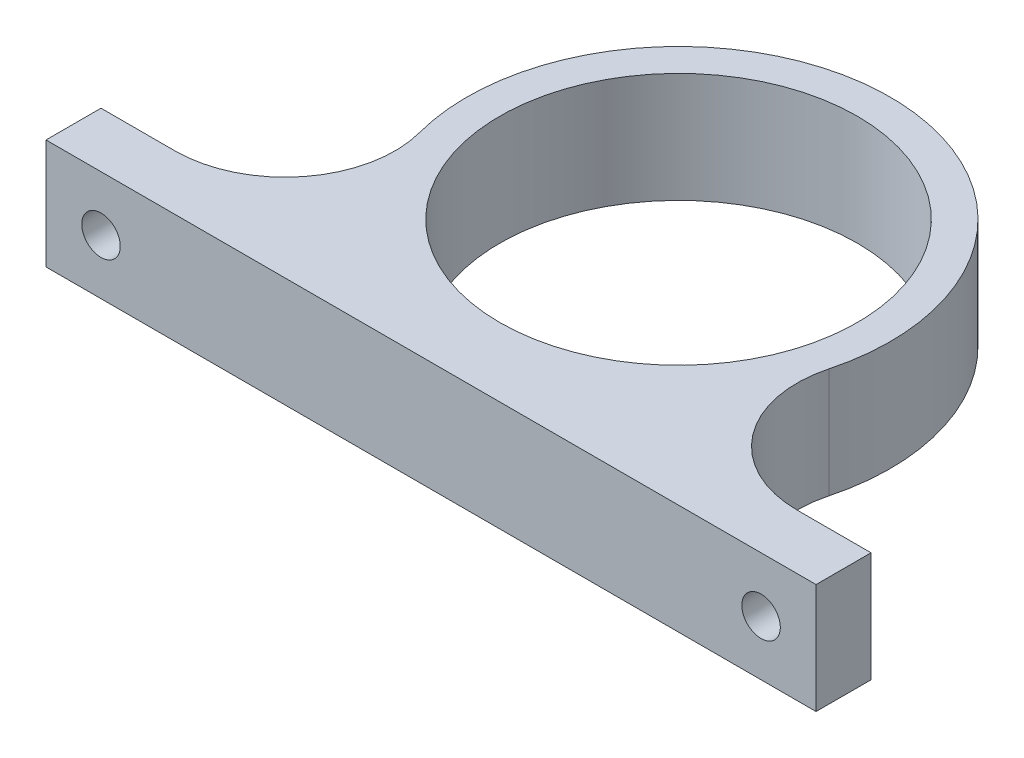
SolidWorks part; units mm, degrees
ref_plane "Front Plane" through (0, 0, 0) normal (0, 0, 1) x (1, 0, 0)
ref_plane "Top Plane" through (0, 0, 0) normal (0, 1, 0) x (1, 0, 0)
ref_plane "Right Plane" through (0, 0, 0) normal (1, 0, 0) x (0, 0, -1)
sketch "Sketch1" plane through (0, 0, 0) normal (0, 1, 0) x (1, 0, 0)
  circle A0 centre (0, 0) radius 16.25
  circle A1 centre (0, 0) radius 19.25
  dimension "D1" = 32.5
  dimension "D2" = 3
extrude "Boss-Extrude1" add sketch "Sketch1" along normal blind 10
sketch "Sketch2" plane through (0, 0, 0) normal (0, 1, 0) x (1, 0, 0)
  line L1 (35, -22.5) -> (-35, -22.5)
  line L2 (35, -22.5) -> (35, -17.5)
  line L3 (35, -17.5) -> (-35, -17.5)
  line L4 (-35, -22.5) -> (-35, -17.5)
  line L5 (35, -22.5) -> (-35, -17.5) construction
  line L6 (35, -17.5) -> (-35, -22.5) construction
  point P0 (0, -20)
  point P5 (0, 0)
  dimension "D1" = 70
  dimension "D2" = 5
  dimension "D3" = 20
extrude "Boss-Extrude2" add sketch "Sketch2" along normal up to surface (10 mm away) up to face at (0, 10, 19.25)
fillet "Fillet1" radius 10 2 edges at (-8.0195, 5, 17.5) (8.0195, 5, 17.5)
sketch "Sketch3" plane through (0, 0, 17.5) normal (0, 0, -1) x (-1, 0, 0)
  line L0 (-35, 10) -> (-35, 0) construction
  line L1 (35, 10) -> (35, 0) construction
  circle A0 centre (30, 5) radius 1.75
  circle A1 centre (-30, 5) radius 1.75
  point P4 (-35, 5)
  point P5 (0, 0)
  dimension "D1" = 3.5
  dimension "D2" = 5
  dimension "D3" = 5
extrude "Cut-Extrude1" cut sketch "Sketch3" against normal through all
